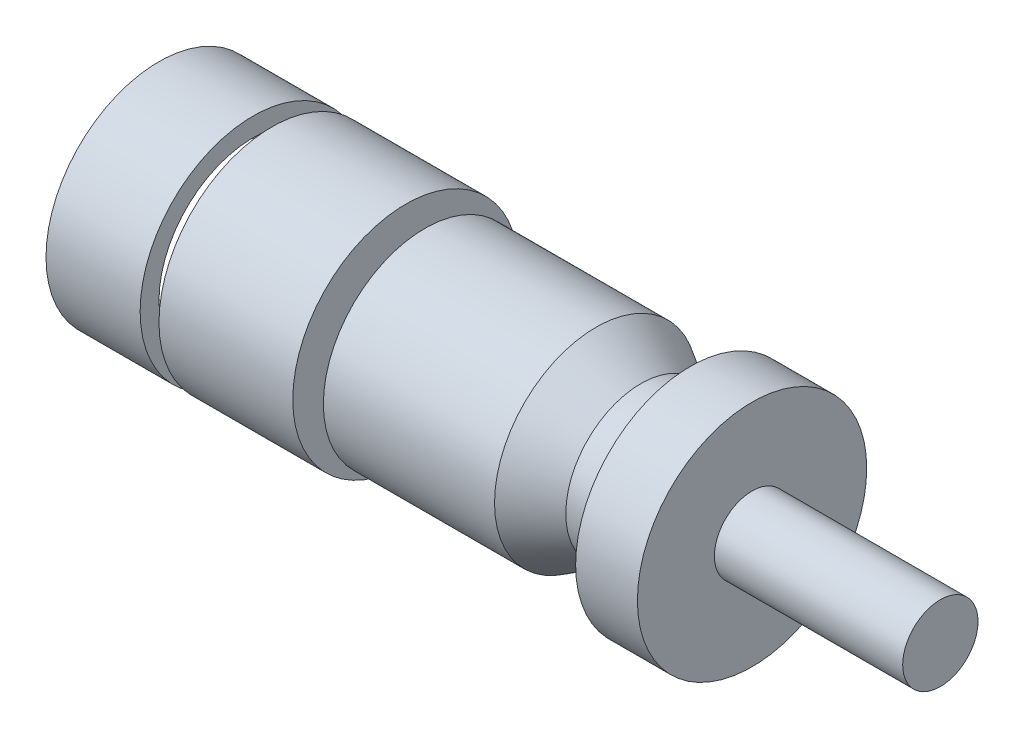
SolidWorks part; units mm, degrees
ref_plane "前视基准面" through (0, 0, 0) normal (0, 0, 1) x (1, 0, 0)
ref_plane "上视基准面" through (0, 0, 0) normal (0, 1, 0) x (1, 0, 0)
ref_plane "右视基准面" through (0, 0, 0) normal (1, 0, 0) x (0, 0, -1)
sketch "草图1" plane through (0, 0, 0) normal (0, 0, 1) x (1, 0, 0)
  line L0 (0, 0) -> (0, 12)
  line L1 (0, 12) -> (10, 12)
  line L2 (10, 12) -> (10, 5.1714)
  line L3 (10, 5.1714) -> (12, 5.1714)
  line L4 (12, 12) -> (26.2136, 12)
  line L5 (46.4383, 10.7952) -> (51.1946, 7.9811)
  line L6 (51.1946, 7.9811) -> (56.4378, 7.9811)
  line L8 (56.4378, 7.9811) -> (56.4378, 12.1796)
  line L9 (56.4378, 12.1796) -> (63, 12.1796)
  line L10 (63, 12.1796) -> (63, 0)
  line L11 (12, 5.1714) -> (12, 12)
  line L12 (0, 0) -> (63, 0)
  line L13 (26.2136, 12) -> (26.2136, 5.1714)
  line L14 (26.2136, 5.1714) -> (28.2581, 5.1714)
  line L15 (28.2581, 5.1714) -> (28.2581, 10.7952)
  line L16 (28.2581, 10.7952) -> (46.4383, 10.7952)
  dimension "D1" = 63
  dimension "D2" = 10
  dimension "D3" = 2
  dimension "D4" = 12
revolve "旋转1" add sketch "草图1" angle 360 about L12
sketch "草图2" plane through (0, 0, 0) normal (-1, 0, 0) x (0, 0, 1)
  circle A0 centre (0, 0) radius 10
  dimension "D1" = 20
extrude "切除-拉伸1" cut sketch "草图2" against normal blind 10
sketch "草图3" plane through (63, 0, 0) normal (1, 0, 0) x (0, 0, -1)
  circle A0 centre (0, 0) radius 4
  dimension "D1" = 8
extrude "凸台-拉伸1" add sketch "草图3" along normal blind 20
